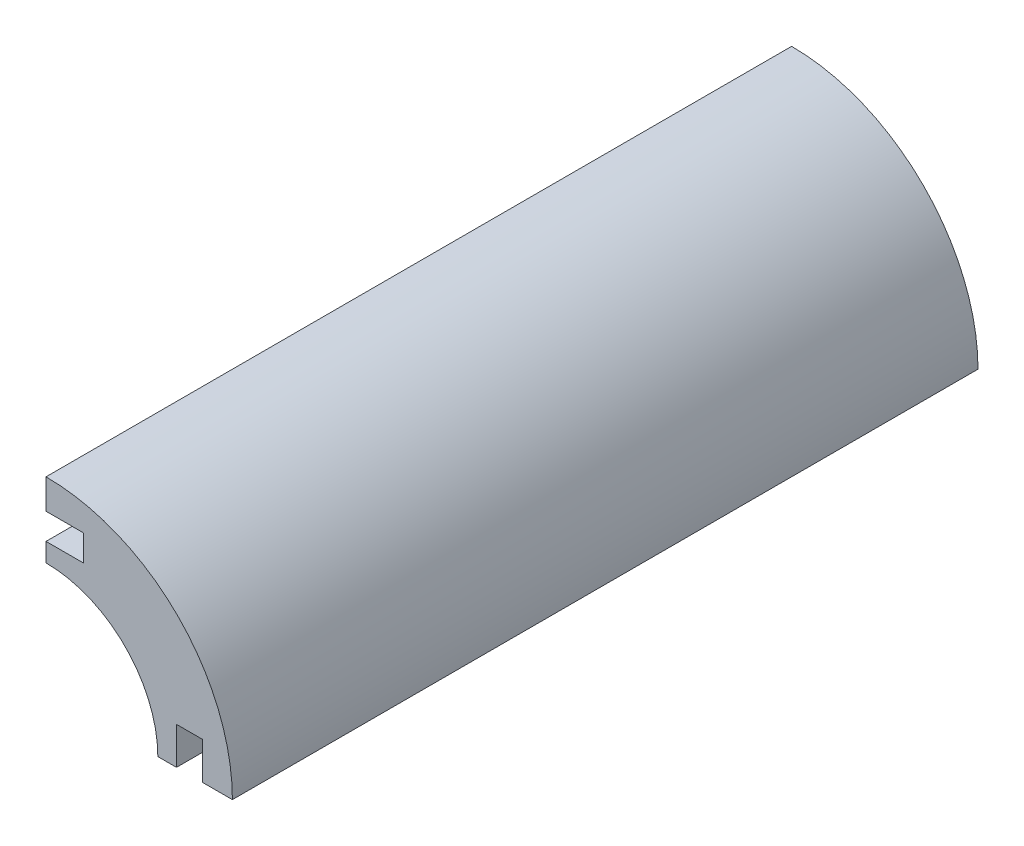
SolidWorks part; units mm, degrees
ref_plane "Plan de face" through (0, 0, 0) normal (0, 0, 1) x (1, 0, 0)
ref_plane "Plan de dessus" through (0, 0, 0) normal (0, 1, 0) x (1, 0, 0)
ref_plane "Plan de droite" through (0, 0, 0) normal (1, 0, 0) x (0, 0, -1)
sketch "Esquisse2" plane through (0, 0, 0) normal (0, 0, 1) x (1, 0, 0)
  line L2 (30, 0) -> (35, 0)
  line L3 (35, 0) -> (35, 10)
  line L4 (35, 10) -> (42, 10)
  line L5 (42, 10) -> (42, 0)
  line L6 (42, 0) -> (50, 0)
  line L7 (0, 50) -> (0, 42)
  line L8 (0, 42) -> (10, 42)
  line L9 (10, 42) -> (10, 35)
  line L10 (10, 35) -> (0, 35)
  line L11 (0, 35) -> (0, 30)
  arc A0 (50, 0) -> (0, 50) centre (0, 0) ccw
  arc A1 (0, 30) -> (30, 0) centre (0, 0) cw
  dimension "D2" = 30
  dimension "D3" = 50
  dimension "D1" = 5
  dimension "D4" = 8
  dimension "6.5" = 5
  dimension "D5" = 7
  dimension "D6" = 10
  dimension "D7" = 7
  dimension "D8" = 10
  dimension "D9" = 8
extrude "Boss.-Extru.1" add sketch "Esquisse2" against normal blind 200
sketch "Esquisse24" plane through (0, 0, -200) normal (0, 0, -1) x (-1, 0, 0)
  line L0 (-21.2132, 21.2132) -> (-35.3553, 35.3553) construction
  arc A0 (0, 30) -> (-30, 0) centre (0, 0) ccw construction
  arc A1 (0, 50) -> (-50, 0) centre (0, 0) ccw construction
  point P8 (-28.2843, 28.2843)
  point P9 (0, 0)
  point P10 (0, 0)
hole_wizard "Dégagement M3.52" positions "Esquisse26" profile "Esquisse25" hole size "M3.5" standard "ISO"
sketch "Esquisse26" plane through (0, 0, -200) normal (0, 0, -1) x (-1, 0, 0)
  point P0 (-28.2843, 28.2843)
  point P4 (-22.2751, 29.2577)
  point P6 (0, 0)
  point P7 (-28.2843, 28.2843)
sketch "Esquisse25" plane through (28.2843, 28.2843, -200) normal (1, 0, 0) x (0, 1, 0)
  line L0 (0, 0) -> (0, 51.2618)
  line L1 (0, 51.2618) -> (2.1, 50)
  line L2 (2.1, 50) -> (2.1, 0)
  line L5 (2.1, 0) -> (0, 0)
  line L10 (0, 51.2618) -> (-2.1, 50) construction
  line L11 (0, -6.35) -> (0, 107.95) construction
  dimension "Diamètre du perçage" = 4.2
  dimension "Profondeur du perçage" = 50
  dimension "Angle de pointe" = 118
